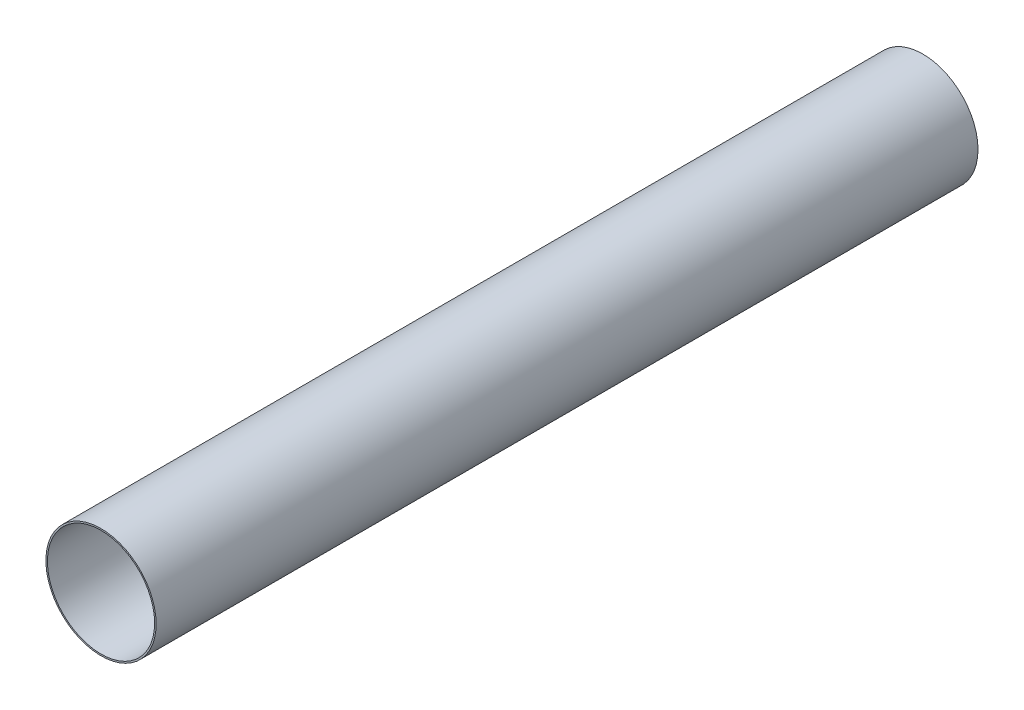
SolidWorks part; units mm, degrees
ref_plane "Plan de face" through (0, 0, 0) normal (0, 0, 1) x (1, 0, 0)
ref_plane "Plan de dessus" through (0, 0, 0) normal (0, 1, 0) x (1, 0, 0)
ref_plane "Plan de droite" through (0, 0, 0) normal (1, 0, 0) x (0, 0, -1)
sketch "Esquisse2" plane through (0, 0, 0) normal (0, 0, 1) x (1, 0, 0)
  circle A0 centre (0, 0) radius 78.359
  circle A1 centre (0, 0) radius 76.2
  dimension "D1" = 156.718
  dimension "D2" = 152.4
extrude "Boss.-Extru.1" add sketch "Esquisse2" along normal blind 1168.4
